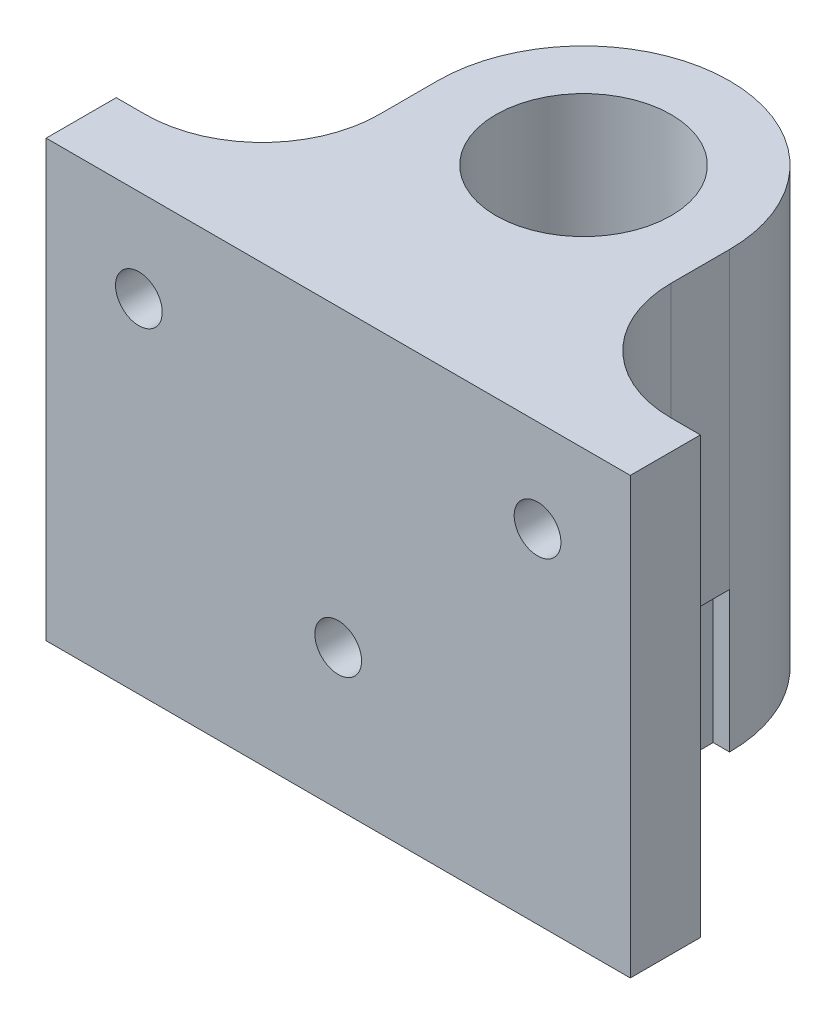
SolidWorks part; units mm, degrees
ref_plane "Front Plane" through (0, 0, 0) normal (0, 0, 1) x (1, 0, 0)
ref_plane "Top Plane" through (0, 0, 0) normal (0, 1, 0) x (1, 0, 0)
ref_plane "Right Plane" through (0, 0, 0) normal (1, 0, 0) x (0, 0, -1)
sketch "Profile-Sketch1" plane through (0, 0, 0) normal (0, 1, 0) x (1, 0, 0)
  line L0 (-25, -21) -> (25, -21)
  line L1 (25, -21) -> (25, -15)
  line L2 (-25, -21) -> (-25, -15)
  line L3 (-25, -15) -> (-22.5, -15)
  line L4 (-12.5, -5) -> (-12.5, 0)
  line L5 (25, -15) -> (22.5, -15)
  line L6 (12.5, -5) -> (12.5, 0)
  circle A0 centre (0, 0) radius 7.5
  arc A6 (12.5, 0) -> (-12.5, 0) centre (0, 0) ccw
  arc A7 (22.5, -15) -> (12.5, -5) centre (22.5, -5) cw
  arc A8 (-12.5, -5) -> (-22.5, -15) centre (-22.5, -5) cw
  dimension "D1" = 15
  dimension "D2" = 12.5
  dimension "D7" = 10
  dimension "D3" = 50
  dimension "D4" = 25
  dimension "D5" = 21
  dimension "D6" = 6
extrude "Profile-Boss-Extrude2" add sketch "Profile-Sketch1" along normal blind 37.2599
sketch "FasteningHoleSketch3" plane through (0, 0, 21) normal (0, 0, 1) x (1, 0, 0)
  line L0 (25, 37.2599) -> (25, 0) construction
  line L1 (-25, 37.2599) -> (-25, 0) construction
  line L2 (-25, 0) -> (25, 0) construction
  circle A2 centre (-17.0625, 29.3224) radius 2
  circle A3 centre (17.0625, 29.3224) radius 2
  dimension "D3" = 4
  dimension "D6" = 7.9375
  dimension "D2" = 29.3224
  dimension "D1" = 7.9375
extrude "FasteningHoleCut-Extrude8" cut sketch "FasteningHoleSketch3" against normal through all
sketch "LM8UUFasteningHoleSketch5" plane through (0, 0, 21) normal (0, 0, 1) x (1, 0, 0)
  line L0 (25, 37.2599) -> (25, 0) construction
  line L1 (-25, 0) -> (25, 0) construction
  line L2 (-25, 37.2599) -> (25, 37.2599) construction
  circle A0 centre (0, 12) radius 2
  circle A1 centre (-17.0625, 29.3224) radius 2 construction
  dimension "D1" = 25
  dimension "D2" = 12
  dimension "D3" = 25.2599
extrude "LM8UUFasteningHoleCut-Extrude9" cut sketch "LM8UUFasteningHoleSketch5" against normal through all
sketch "Sketch1" plane through (0, 0, 0) normal (0, -1, 0) x (1, 0, 0)
  line L0 (13.9, 12.85) -> (16.3638, 12.85)
  line L1 (11.1, 12.85) -> (13.9, 12.85)
  line L2 (11.1, 12.85) -> (11.1, 0)
  line L3 (11.1, 0) -> (13.9, 0)
  line L4 (13.9, 10.1029) -> (13.9, 0)
  line L5 (16.3638, 12.85) -> (13.9, 10.1029)
  arc A0 (22.5, 15) -> (12.5, 5) centre (22.5, 5) ccw construction
  dimension "D2" = 12.85
  dimension "D3" = 2.8
  dimension "D1" = 1.4
extrude "MicroSwitchCut-Extrude1" cut sketch "Sketch1" against normal blind 12.05
sketch "MicroSwitchMountingHoleSketch2" plane through (11.1, 0, 0) normal (1, 0, 0) x (0, 0, -1)
  line L0 (-12.85, 0) -> (-12.85, 12.05) construction
  line L1 (0, 12.05) -> (0, 0) construction
  line L3 (-12.85, 12.05) -> (-5, 12.05) construction
  circle A0 centre (-9.6, 5.05) radius 1.5
  circle A1 centre (-3.25, 5.05) radius 1.5
  dimension "D1" = 3
  dimension "D2" = 3.25
  dimension "D3" = 3.25
  dimension "D4" = 7
extrude "MicroSwitchMountingHoleCut-Extrude2" cut sketch "MicroSwitchMountingHoleSketch2" against normal blind 3.1
equation "\"RailThickness\"= .125in'Spec"
equation "\"LM8UUDiameter\"= 15mm"
equation "\"MidLeftOrRightSideRailHeight\"= 2.0in"
equation "\"RodStabilizerLength\"= 50mm"
equation "\"HoleOffsetFromEdge\"= \"RailThickness\" * 2.5"
equation "\"StepperMountingHoleOffsetFromItsSide\"= 5.5mm'Spec"
equation "\"StepperMountingHoleOffsetFromLeftOrRightSide\"= \"StepperMountingHoleOffsetFromItsSide\" + \"RailThickness\""
equation "\"StepperMountingHoleDistance\"= 31mm'Spec"
equation "\"LM8UUHeight\"= 24mm'Spec"
equation "\"ZAxisLeadScrewLength\"= 200mm"
equation "\"LegHeight\"= 70mm'Space needed for PSU/Stepper/Electronics"
equation "\"V1 BottomOfLowerRail\"= \"LegHeight\""
equation "\"StepperShaftLength\"= 24mm'Pulley will be attached to the end"
equation "\"V2 ToBedAtTopOfZAxis\"= \"V1 BottomOfLowerRail\" - \"LowerEnclosureThickness\" + \"StepperShaftLength\" + \"ZAxisLeadScrewLength\" - \"LM8UUHeight\" / 2'Equals 277"
equation "\"HotEndToTopOfXAxisGB\"= 71.68487mm'Equals 71.68487. Measured after installed onto X-Axis linear rail guide block"
equation "\"TopOfGBToBottomOfLinearRail\"= \"LinearGBWidth\" / 2 + \"LinearRailWidth\" / 2'Equals 19.5"
equation "\"LinearGBWidth\"= 27mm'Spec"
equation "\"V5 ToBottomOfXAxisLinearRail\"= \"V4 ToTopOfBuildPlate/HotEndTip\" + \"HotEndToTopOfXAxisGB\" - \"TopOfGBToBottomOfLinearRail\"'Equals 352.18487"
equation "\"LinearRailWidth\"= 12mm'Spec"
equation "\"V6 ToMiddleOfYAxisGantryBlock\"= \"V5 ToBottomOfXAxisLinearRail\" - \"GABHeight\" / 2'Equals 334.18487"
equation "\"GABUpperHeight\"= 4mm"
equation "\"GABMidWallHeight\"= 28mm'Must equal 28 or changes alignment"
equation "\"BedToBuildPlateStandoffLength\"= 15mm"
equation "\"BuildPlateHeight\"= 8mm'Spec"
equation "\"V4 ToTopOfBuildPlate/HotEndTip\"= \"V2 ToBedAtTopOfZAxis\" + \"BedToBuildPlateStandoffLength\" + \"BuildPlateHeight\""
equation "\"RodStabilizerHeight\"= \"V8 ToBottomOfMidSideRail\" - \"V2 ToBedAtTopOfZAxis\" + \"HoleOffsetFromEdge\" * 2"
equation "\"LowerEnclosureThickness\"= 5mm"
equation "\"D1@Profile-Sketch1\" = \"LM8UUDiameter\""
equation "\"D3@Profile-Sketch1\" = \"RodStabilizerLength\""
equation "\"D4@Profile-Sketch1\" = \"RodStabilizerLength\" / 2"
equation "\"RodStabilizerWidthFromMidRailToZAxisRodCenter\"= \"StepperMountingHoleOffsetFromLeftOrRightSide\" + \"StepperMountingHoleDistance\" / 2 - \"RailThickness\""
equation "\"StandardWallThickness\"= 3mm"
equation "\"D6@Profile-Sketch1\" = \"StandardWallThickness\" * 2"
equation "\"D1@Profile-Boss-Extrude2\"= \"RodStabilizerHeight\""
equation "\"D6@FasteningHoleSketch3\"=\"HoleOffsetFromEdge\""
equation "\"D2@LM8UUFasteningHoleSketch5\"=\"LM8UUHeight\"/2"
equation "\"V8 ToTopOfMidSideRail\"= \"V6 ToMiddleOfYAxisGantryBlock\" + \"MidSideRailVerticalOffset\"'Equals 349.18487"
equation "\"D5@Profile-Sketch1\"=\"RodStabilizerWidthFromMidRailToZAxisRodCenter\""
equation "\"RodStabilizerMountingHoleYOffsetFromBottom\"= \"RodStabilizerHeight\" - \"HoleOffsetFromEdge\""
equation "\"D2@FasteningHoleSketch3\"=\"RodStabilizerMountingHoleYOffsetFromBottom\""
equation "\"D3@FasteningHoleSketch3\"=\"M3HeatInsertHoleDiameter\""
equation "\"GABLowerHeight\"= 4mm"
equation "\"GABHeight\"= \"GABLowerHeight\" + \"GABMidWallHeight\" + \"GABUpperHeight\""
equation "\"V8 ToBottomOfMidSideRail\"= \"V8 ToTopOfMidSideRail\" - \"MidLeftOrRightSideRailHeight\"'Equals 298.38487"
equation "\"D1@LM8UUFasteningHoleSketch5\"=\"RodStabilizerLength\"/2"
equation "\"MidSideRailVerticalOffset\"= \"LinearRailWidth\" + 3mm'Allows space for RodStabilizer to attach to bottom of MidSideRail"
equation "\"M3HeatInsertHoleDiameter\"= 4mm'Spec"
equation "\"MicroSwitchLength\"= 12.85mm"
equation "\"MicroSwitchHeight\"= 6.55mm"
equation "\"MicroSwitchMountHoleOffsetFromSide\"= 3.25mm"
equation "\"MicroSwitchDepth\"= 2.8mm"
equation "\"MicroSwitchTerminalHeight\"= 3.5mm"
equation "\"D2@Sketch1\"=\"MicroSwitchLength\""
equation "\"D3@Sketch1\"=\"MicroSwitchDepth\""
equation "\"D1@Sketch1\"=\"MicroSwitchDepth\"/2"
equation "\"D1@MicroSwitchCut-Extrude1\" = \"MicroSwitchHeight\" + \"MicroSwitchTerminalHeight\" + \"MicroSwitchExtraMountingHeight\""
equation "\"M2HeatInsertHoleDiameter\"= 3mm'Spec"
equation "\"D1@MicroSwitchMountingHoleSketch2\" = \"M2HeatInsertHoleDiameter\""
equation "\"D2@MicroSwitchMountingHoleSketch2\" = \"MicroSwitchMountHoleOffsetFromSide\""
equation "\"D3@MicroSwitchMountingHoleSketch2\" = \"MicroSwitchMountHoleOffsetFromSide\""
equation "\"MicroSwitchMountHoleOffsetFromBottom\"= 1.5mm"
equation "\"D4@MicroSwitchMountingHoleSketch2\"= \"MicroSwitchTerminalHeight\" + \"MicroSwitchExtraMountingHeight\" + \"MicroSwitchMountHoleOffsetFromBottom\""
equation "\"D1@MicroSwitchMountingHoleCut-Extrude2\"=\"M2HeatInsertHoleDepth\""
equation "\"MicroSwitchExtraMountingHeight\"= 2mm"
equation "\"M2HeatInsertHoleDepth\" = 3.1mm'Spec"
